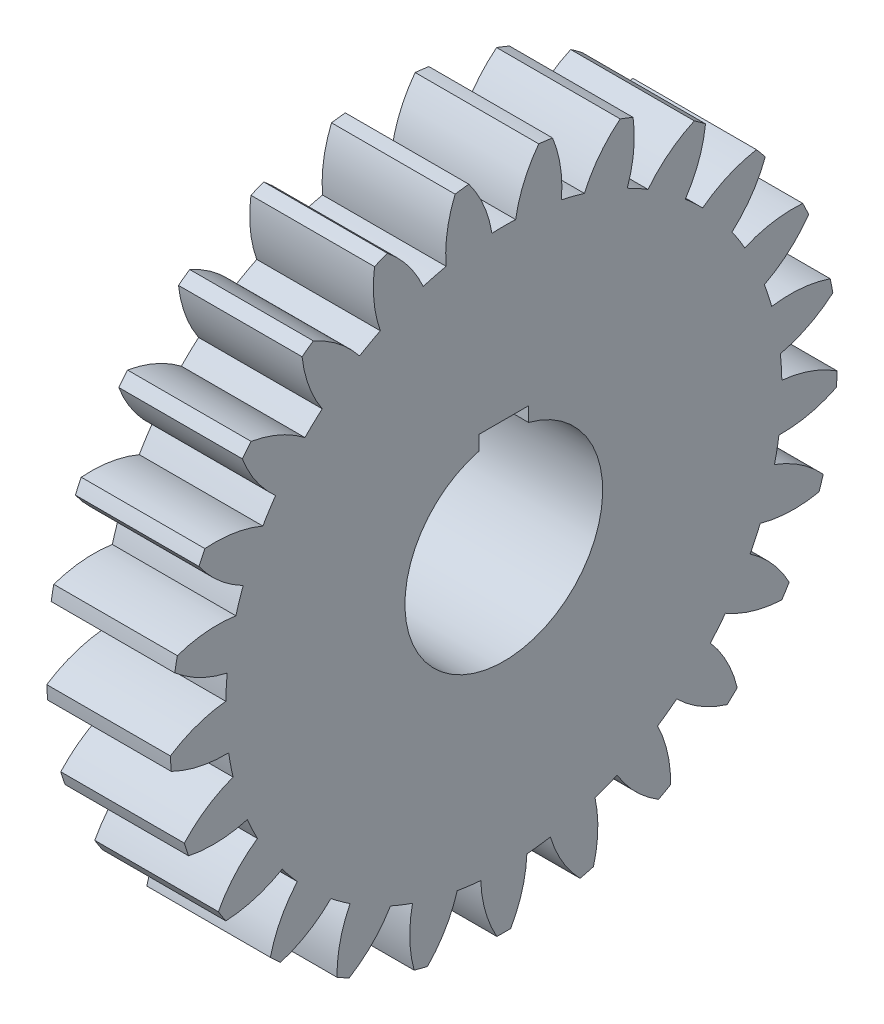
SolidWorks part; units mm, degrees
material "1023 Carbon Steel Sheet (SS)"
ref_plane "Plane1" through (0, 0, 0) normal (0, 0, 1) x (1, 0, 0)
ref_plane "Plane2" through (0, 0, 0) normal (0, 1, 0) x (1, 0, 0)
ref_plane "Plane3" through (0, 0, 0) normal (1, 0, 0) x (0, 0, -1)
sketch "HoldingSke" plane through (0, 0, 0) normal (0, 1, 0) x (1, 0, 0)
  line L0 (0, 0) -> (0.0363, -0.0169)
  line L1 (-15, 0) -> (100, 0) construction
  line L2 (0, 0) -> (-2.1039, 2.3779)
  line L3 (0, 0) -> (-11.863, 4.5341)
  line L4 (0, 0) -> (7.8269, 3.6497)
  line L5 (0, 0) -> (-159.282, -59.4075)
  line L6 (0, 0) -> (-103.6204, -69.913)
  line L7 (-2.1039, 2.3779) -> (34.4885, 168.393)
  line L8 (-76.2, 54.61) -> (-64.8, 54.61)
  line L9 (-71.009, 38.7566) -> (-53.1078, 45.2721)
  line L10 (-76.2, 71.12) -> (104.1128, 71.12)
  line L11 (0, 0) -> (-125, 0)
  line L12 (-76.2, 101.6) -> (-75.26, 101.6)
  line L13 (24.9733, 27.94) -> (52.9518, 28.4284)
  line L14 (24.9733, 27.94) -> (24.9743, 27.94)
  line L15 (24.9733, 27.94) -> (100.4006, 29.5858)
  line L16 (-63.627, -25) -> (-12.827, -25)
  circle A0 centre (0, 0) radius 100
  circle A1 centre (0, 0) radius 175
  circle A2 centre (0, 0) radius 175
  circle A3 centre (0, 0) radius 100
  dimension "Bore" = 200
  dimension "MBD" = 200
  dimension "Pitch" = 0.04
  dimension "T_dim" = 11.4
  dimension "Ap" = 20
  dimension "H" = 19.05
  dimension "Pitch_radius" = 180.3128
  dimension "Backlash" = 0.94
  dimension "Addendum_fac" = 1
  dimension "Dedendum_fac" = 1.25
  dimension "Clearance_fac" = 0.25
  dimension "Dedendum_add" = 0.001
  dimension "Module" = 25
sketch "BasProSke" plane through (0, 0, 0) normal (0, 1, 0) x (1, 0, 0)
  line L0 (-10, 0) -> (60, 0) construction
  line L1 (0, 0) -> (0, 337.5)
  line L2 (0, 0) -> (125, 0)
  line L3 (125, 0) -> (125, 337.5)
  line L4 (125, 337.5) -> (0, 337.5)
revolve "Base-Revolve" add sketch "BasProSke" angle 360 about L0
sketch "TooCutSke" plane through (0, 0, 0) normal (1, 0, 0) x (0, 0, -1)
  line L1 (0, 0) -> (0, 107) construction
  line L2 (0, 0) -> (-21.2665, 311.7755) construction
  line L3 (0, 0) -> (-78.2035, 619.0448) construction
  line L4 (-21.2665, 311.7755) -> (-39.1018, 309.5224) construction
  arc A0 (11.9904, 280.9933) -> (-11.9904, 280.9933) centre (0, 0) ccw
  arc A1 (35.3567, 335.6684) -> (-35.3567, 335.6684) centre (0, 0) ccw
  circle A2 centre (0, 0) radius 312.5 construction
  circle A3 centre (0, 0) radius 293.6539 construction
  arc A4 (-11.9904, 280.9933) -> (-35.3567, 335.6684) centre (-135.3185, 260.6176) ccw
  arc A5 (35.3567, 335.6684) -> (11.9904, 280.9933) centre (135.3185, 260.6176) ccw
extrude "ToothCut" cut sketch "TooCutSke" along normal through all
fillet "Breaks" [suppressed] radius 0.5
fillet "RootFillets" [suppressed] radius 6.251
pattern_circular "TeethCuts" count 25 every 14.4 about axis through (-10, 0, 0) along (1, 0, 0) of "ToothCut", "RootFillets", "Breaks"
sketch "HubNeaOneSke" plane through (0, 0, 0) normal (-1, 0, 0) x (0, 0, 1)
  circle A0 centre (0, 0) radius 175
extrude "HubNearOne" add sketch "HubNeaOneSke" along normal blind 45.0001
sketch "HubNeaBotSke" plane through (0, 0, 0) normal (-1, 0, 0) x (0, 0, 1)
  circle A0 centre (0, 0) radius 175
extrude "HubNearBoth" [suppressed] add sketch "HubNeaBotSke" along normal blind 22.5
ref_plane "FarPln" through (125, 0, 0) normal (1, 0, 0) x (0, 0, -1)
sketch "HubFarSke" plane through (125, 0, 0) normal (1, 0, 0) x (0, 0, -1)
  circle A0 centre (0, 0) radius 175
extrude "HubFar" [suppressed] add sketch "HubFarSke" along normal blind 22.5
sketch "BorSke" plane through (0, 0, 0) normal (1, 0, 0) x (0, 0, -1)
  circle A0 centre (0, 0) radius 100
  dimension "Diameter" = 200
extrude "Bore" cut sketch "BorSke" along normal mid plane 340.0001
sketch "KeySke" plane through (0, 0, 0) normal (1, 0, 0) x (0, 0, -1)
  line L0 (-25, 0) -> (-25, 111.4)
  line L1 (-25, 111.4) -> (25, 111.4)
  line L2 (25, 111.4) -> (25, 0)
  line L3 (0, 0) -> (0, 34) construction
  line L4 (-25, 0) -> (25, 0)
  dimension "Offset" = 111.4
  dimension "Width" = 50
extrude "Keyway" cut sketch "KeySke" along normal mid plane 340.0001
pattern_circular "Keyway2" [suppressed] count 2 every 90 about axis through (-10, 0, 0) along (1, 0, 0)
equation "' \"Module@HoldingSke\" = 6.35"
equation "' \"Num_teeth@HoldingSke\" = 12"
equation "' \"Ap@HoldingSke\" =  20"
equation "' \"Ap@HoldingSke\" = 20"
equation "' \"Width@HoldingSke\" = 0.5 * 25.4"
equation "' \"Hub_dia@HoldingSke\"= 1 * 25.4"
equation "' \"Hub_dia@HoldingSke\" = 1 * 25.4"
equation "' \"Overall_len@HoldingSke\" = 1.0 * 25.4"
equation "' \"Bore@HoldingSke\" = 0.75 * 25.4"
equation "' \"T_dim@HoldingSke\" = 0.1 * 25.4"
equation "' \"Width@KeySke\" = 0.25 * 25.4"
equation "' \"Show_teeth@HoldingSke\" = 13"
equation "' \"Backlash@HoldingSke\" = 0.009 * 25.4"
equation "' \"Addendum_fac@HoldingSke\" = 1.0"
equation "' \"Dedendum_fac@HoldingSke\" = 1.25"
equation "' \"Dedendum_add@HoldingSke\" = 0.00005 * 25.4"
equation "' \"Clearance_fac@HoldingSke\" = 0.25"
equation "\"Pitch@HoldingSke\" = 1 / \"Module@HoldingSke\""
equation "\"Overcut_dia@TooCutSke\" = (\"Num_teeth@HoldingSke\" + 2 * \"Addendum_fac@HoldingSke\") / \"Pitch@HoldingSke\" + 0.002 * 25.4"
equation "\"Pitch_dia@TooCutSke\" = \"Num_teeth@HoldingSke\" / \"Pitch@HoldingSke\""
equation "\"Base_dia@TooCutSke\" = \"Num_teeth@HoldingSke\" / \"Pitch@HoldingSke\" * cos((\"Ap@HoldingSke\"  * 3.14159265 / 180))"
equation "\"Root_dia@TooCutSke\" = (\"Num_teeth@HoldingSke\" + 2) / \"Pitch@HoldingSke\" - 2 * (\"Addendum_fac@HoldingSke\" + \"Dedendum_fac@HoldingSke\") / \"Pitch@HoldingSke\" - \"Dedendum_add@HoldingSke\" * 2"
equation "\"Half_ang@TooCutSke\" = 180 / \"Num_teeth@HoldingSke\""
equation "\"Half_CT@TooCutSke\" = \"Num_teeth@HoldingSke\" / \"Pitch@HoldingSke\" * sin((3.14159265 / 2 / \"Num_teeth@HoldingSke\")) / 2 - 7 * \"Backlash@HoldingSke\" / 4"
equation "\"Flank_rad@TooCutSke\" = \"Num_teeth@HoldingSke\" / \"Pitch@HoldingSke\" / 5"
equation "\"Radius@RootFillets\" = \"Clearance_fac@HoldingSke\" / \"Pitch@HoldingSke\" + \"Dedendum_add@HoldingSke\""
equation "\"Break_rad@Breaks\" = 0.02 / \"Pitch@HoldingSke\""
equation "\"Thickness@HoldingSke\" = \"Width@HoldingSke\""
equation "\"OAL@HoldingSke\" = \"Thickness@HoldingSke\""
equation "\"MHD@HoldingSke\" = (\"Num_teeth@HoldingSke\" + 2) / \"Pitch@HoldingSke\" - 2 * (\"Addendum_fac@HoldingSke\" + \"Dedendum_fac@HoldingSke\")  / \"Pitch@HoldingSke\" - \"Dedendum_add@HoldingSke\" * 2"
equation "\"MBD@HoldingSke\" = (\"Num_teeth@HoldingSke\" + 2) / \"Pitch@HoldingSke\" - 2 * (\"Addendum_fac@HoldingSke\" + \"Dedendum_fac@HoldingSke\")  / \"Pitch@HoldingSke\" - \"Dedendum_add@HoldingSke\" * 2 - 0.002 * 25.4"
equation "\"MHD@HoldingSke\" = ((sgn( \"MHD@HoldingSke\" - \"Hub_dia@HoldingSke\" )-1)*( \"MHD@HoldingSke\" - \"Hub_dia@HoldingSke\" ))/-2+ \"Hub_dia@HoldingSke\""
equation "\"MBD@HoldingSke\" = ((sgn( \"MBD@HoldingSke\" - \"Bore@HoldingSke\" )-1)*( \"MBD@HoldingSke\" - \"Bore@HoldingSke\" ))/-2+ \"Bore@HoldingSke\""
equation "\"OAL@HoldingSke\" = ((sgn( \"OAL@HoldingSke\" - \"Overall_len@HoldingSke\" )+1)*( \"OAL@HoldingSke\" - \"Overall_len@HoldingSke\" ))/2 + \"Overall_len@HoldingSke\" + 0.000002 * 25.4"
equation "\"Num_teeth@TeethCuts\" = int( \"Show_teeth@HoldingSke\" ) + 1"
equation "\"Num_teeth@TeethCuts\" = ((sgn( \"Num_teeth@TeethCuts\" - \"Num_teeth@HoldingSke\" )-1)*( \"Num_teeth@TeethCuts\" - \"Num_teeth@HoldingSke\" ))/-2+ \"Num_teeth@HoldingSke\""
equation "\"Num_teeth@TeethCuts\" = ((sgn( \"Num_teeth@TeethCuts\" - 2.0)+1)*( \"Num_teeth@TeethCuts\" - 2.0))/2 +2.0"
equation "\"Angle@TeethCuts\" = 360.0 / \"Num_teeth@HoldingSke\""
equation "\"Diameter@BasProSke\" = (\"Num_teeth@HoldingSke\" + 2 * \"Addendum_fac@HoldingSke\") / \"Pitch@HoldingSke\""
equation "\"Thickness@BasProSke\"  = \"Thickness@HoldingSke\""
equation "' \"Fillet_rad@BasProSke\" =  \"Thickness@HoldingSke\" * 0.05"
equation "' \"Fillet_rad@BasProSke\" = \"Thickness@HoldingSke\" * 0.05"
equation "\"MHD@HoldingSke\" = ((sgn( \"MHD@HoldingSke\" - \"Root_dia@TooCutSke\" )-1)*( \"MHD@HoldingSke\" - \"Root_dia@TooCutSke\" ))/-2+ \"Root_dia@TooCutSke\""
equation "\"Diameter@HubNeaOneSke\" = \"MHD@HoldingSke\""
equation "\"Length@HubNearOne\" = \"OAL@HoldingSke\" - \"Thickness@BasProSke\""
equation "\"Diameter@HubNeaBotSke\" = \"MHD@HoldingSke\""
equation "\"Length@HubNearBoth\" = ( \"OAL@HoldingSke\" - \"Thickness@BasProSke\" ) / 2.0"
equation "\"Thickness@FarPln\" = \"Thickness@BasProSke\""
equation "\"Diameter@HubFarSke\" = \"MHD@HoldingSke\""
equation "\"Length@HubFar\" = ( \"OAL@HoldingSke\" - \"Thickness@BasProSke\" ) / 2.0"
equation "\"Diameter@BorSke\" = \"MBD@HoldingSke\""
equation "\"D1@Bore\" = \"OAL@HoldingSke\" * 2.0"
equation "\"D1@Keyway\" = \"OAL@HoldingSke\" * 2.0"
equation "\"Offset@KeySke\" = \"T_dim@HoldingSke\" + \"MBD@HoldingSke\" / 2.0"
